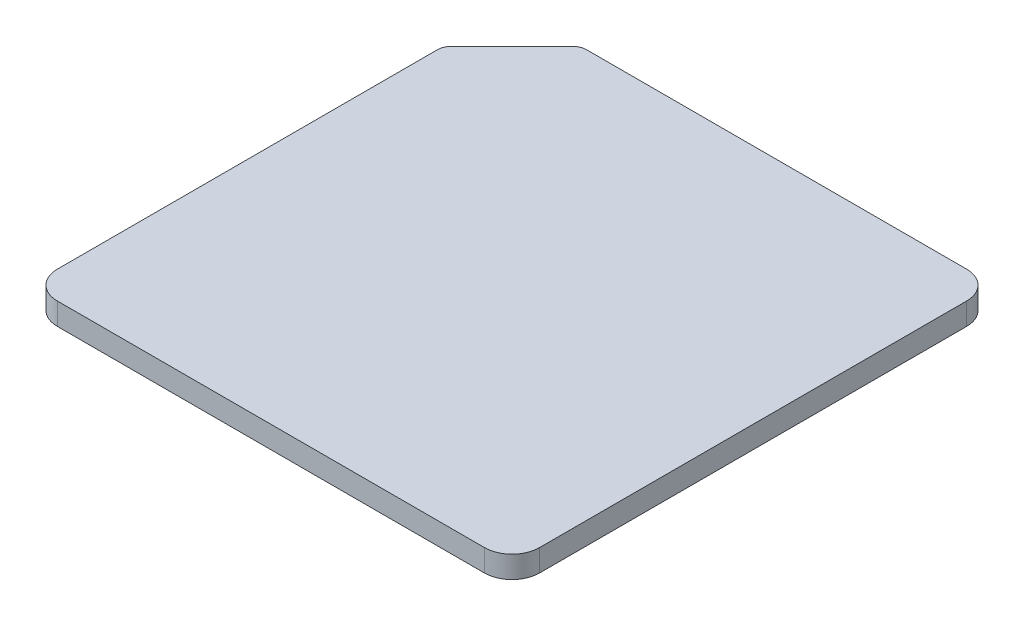
SolidWorks part; units mm, degrees
ref_plane "前视基准面" through (0, 0, 0) normal (0, 0, 1) x (1, 0, 0)
ref_plane "上视基准面" through (0, 0, 0) normal (0, 1, 0) x (1, 0, 0)
ref_plane "右视基准面" through (0, 0, 0) normal (1, 0, 0) x (0, 0, -1)
sketch "草图1" plane through (0, 0, 0) normal (0, 1, 0) x (1, 0, 0)
  line L1 (-17.5, 17.5) -> (17.5, 17.5)
  line L2 (-17.5, 17.5) -> (-17.5, -17.5)
  line L3 (-17.5, -17.5) -> (17.5, -17.5)
  line L4 (17.5, 17.5) -> (17.5, -17.5)
  line L5 (-17.5, 17.5) -> (17.5, -17.5) construction
  line L6 (-17.5, -17.5) -> (17.5, 17.5) construction
  point P0 (0, 0)
  dimension "D1" = 35
  dimension "D2" = 35
extrude "凸台-拉伸1" add sketch "草图1" along normal blind 1.6
chamfer "倒角1" distance 5 angle 45 1 edges at (-17.5, 0.8, -17.5)
fillet "圆角1" radius 1 2 edges at (-17.5, 0.8, -12.5) (-12.5, 0.8, -17.5)
fillet "圆角2" radius 2 3 edges at (17.5, 0.8, -17.5) (17.5, 0.8, 17.5) (-17.5, 0.8, 17.5)
